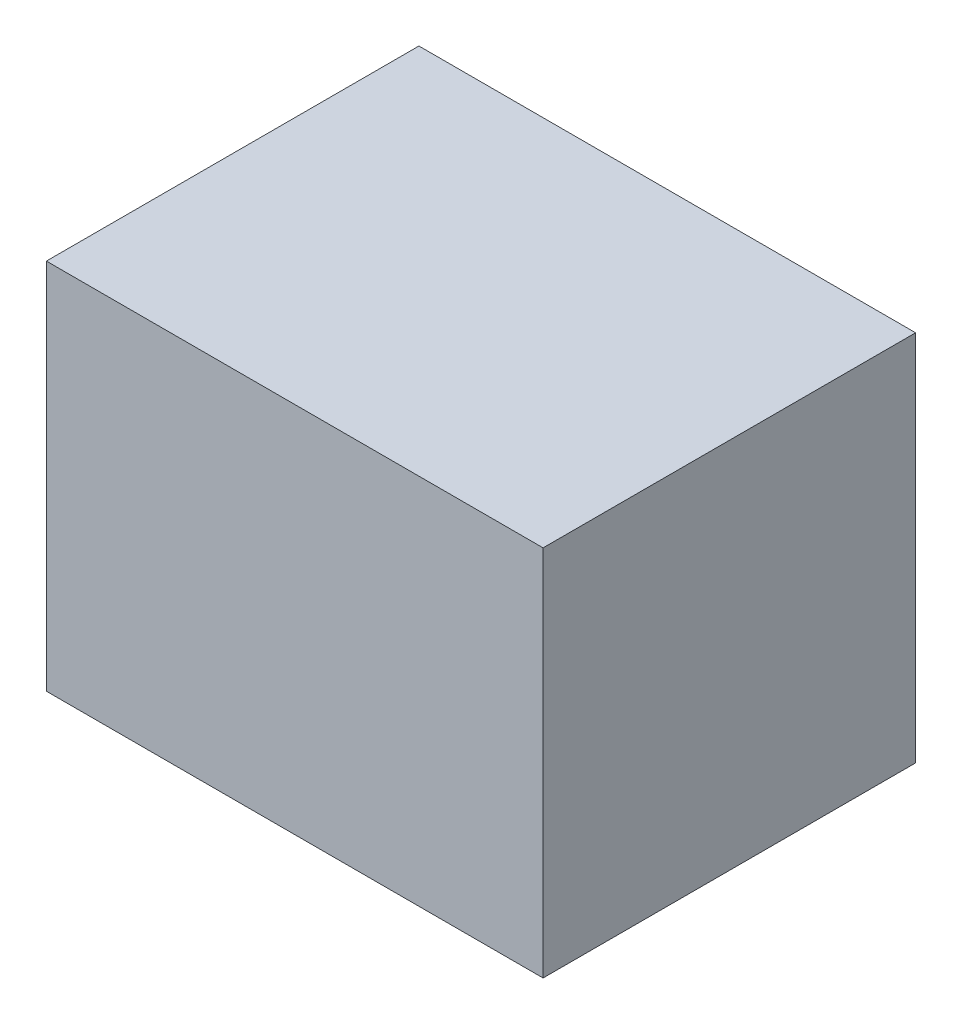
SolidWorks part; units mm, degrees
ref_plane "Front Plane" through (0, 0, 0) normal (0, 0, 1) x (1, 0, 0)
ref_plane "Top Plane" through (0, 0, 0) normal (0, 1, 0) x (1, 0, 0)
ref_plane "Right Plane" through (0, 0, 0) normal (1, 0, 0) x (0, 0, -1)
sketch "Sketch1" plane through (0, 0, 0) normal (0, 1, 0) x (1, 0, 0)
  line L1 (-95.6311, 74.5648) -> (64.3689, 74.5648)
  line L2 (-95.6311, 74.5648) -> (-95.6311, -45.4352)
  line L3 (-95.6311, -45.4352) -> (64.3689, -45.4352)
  line L4 (64.3689, 74.5648) -> (64.3689, -45.4352)
  dimension "D1" = 120
  dimension "D2" = 160
extrude "Boss-Extrude1" add sketch "Sketch1" along normal blind 120
